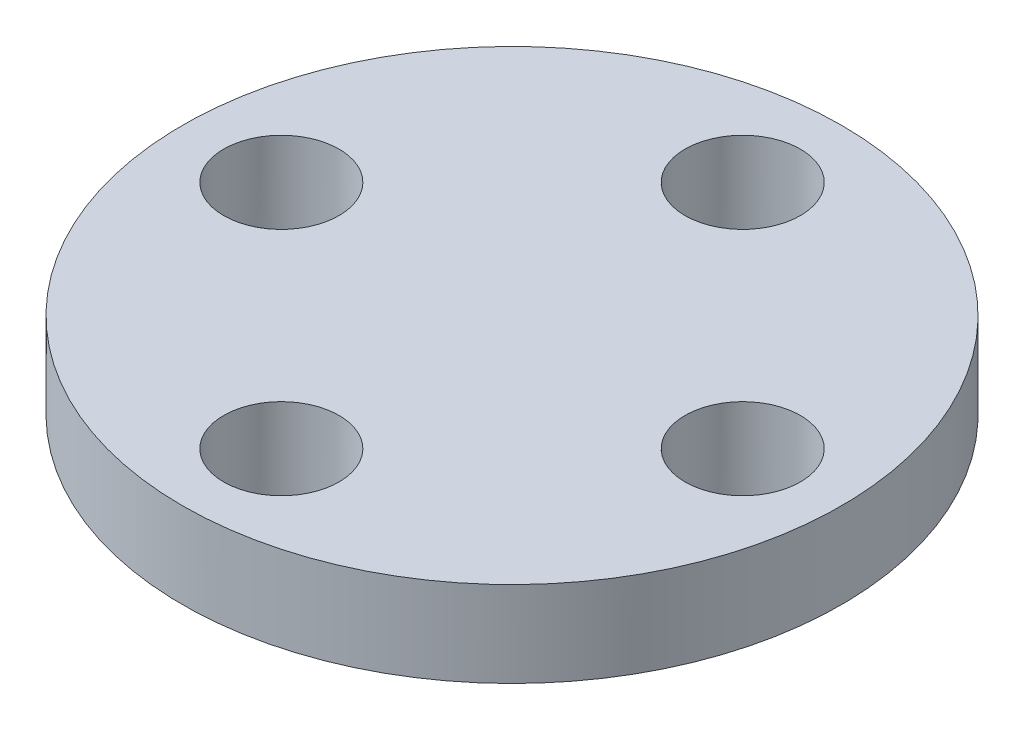
SolidWorks part; units mm, degrees
ref_plane "Front Plane" through (0, 0, 0) normal (0, 0, 1) x (1, 0, 0)
ref_plane "Top Plane" through (0, 0, 0) normal (0, 1, 0) x (1, 0, 0)
ref_plane "Right Plane" through (0, 0, 0) normal (1, 0, 0) x (0, 0, -1)
sketch "Sketch1" plane through (0, 0, 0) normal (0, 1, 0) x (1, 0, 0)
  circle A0 centre (0, 0) radius 10
  dimension "D1" = 20
extrude "Boss-Extrude1" add sketch "Sketch1" along normal blind 4.5
sketch "Sketch2" plane through (0, 0, 0) normal (0, -1, 0) x (1, 0, 0)
  circle A0 centre (0, 0) radius 4.4
  circle A1 centre (0, 0) radius 2.75
  circle A2 centre (0, 0) radius 10 construction
  circle A3 centre (0, 0) radius 10
  circle M1 centre (0, 0) radius 10
  dimension "D1" = 8.8
  dimension "D2" = 5.5
extrude "Cut-Extrude1" cut sketch "Sketch2" against normal blind 1.9 contours A0 M1 | A1
sketch "Sketch4" plane through (0, 4.5, 0) normal (0, 1, 0) x (1, 0, 0)
  line L0 (0, 0) -> (0, 20.0416) construction
  line L1 (0, 0) -> (20.0416, 0) construction
  line L2 (0, 0) -> (0, -20.0416) construction
  line L3 (0, 0) -> (-20.0416, 0) construction
  circle A0 centre (0, 7) radius 1.75
  circle A1 centre (7, 0) radius 1.75
  circle A2 centre (0, -7) radius 1.75
  circle A3 centre (-7, 0) radius 1.75
  point P0 (0, 0)
  point P18 (0, 0)
  dimension "D1" = 3.5
  dimension "D2" = 7
  dimension "D3" = 4
extrude "Cut-Extrude2" cut sketch "Sketch4" against normal through all
sketch "Sketch5" plane through (0, 1.9, 0) normal (0, -1, 0) x (1, 0, 0)
  circle A1 centre (0, 0) radius 2.75
  circle A2 centre (0, 0) radius 2.75
  point P0 (0, 0)
  dimension "D1" = 0
extrude "Cut-Extrude3" cut sketch "Sketch5" against normal blind 1
